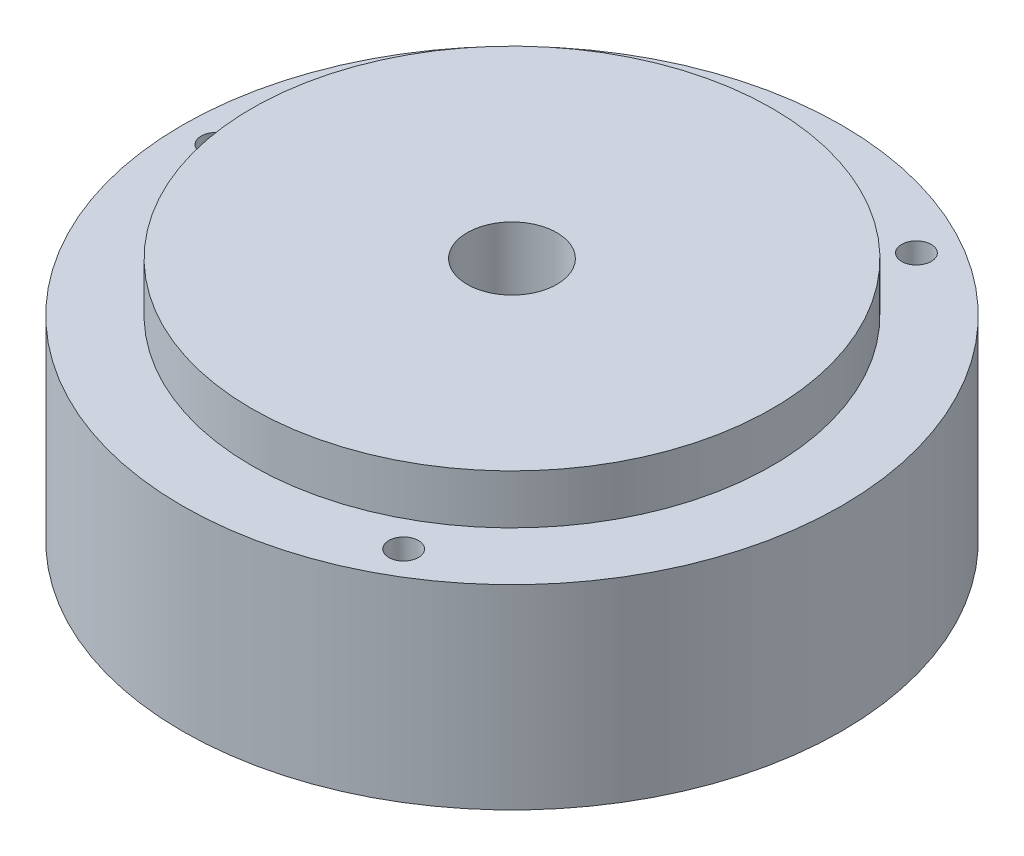
SolidWorks part; units mm, degrees
ref_plane "Alzado" through (0, 0, 0) normal (0, 0, 1) x (1, 0, 0)
ref_plane "Planta" through (0, 0, 0) normal (0, 1, 0) x (1, 0, 0)
ref_plane "Vista lateral" through (0, 0, 0) normal (1, 0, 0) x (0, 0, -1)
sketch "Croquis1" plane through (0, 0, 0) normal (0, 0, 1) x (1, 0, 0)
  line L0 (0, 49.6219) -> (0, -38.8565) construction
  line L2 (73.5, -19.267) -> (73.5, 24.233)
  line L3 (73.5, 24.233) -> (58, 24.233)
  line L4 (58, 24.233) -> (58, 35.233)
  line L5 (58, 35.233) -> (0, 35.233)
  line L6 (0, -29.767) -> (0, 35.233)
  line L7 (73.5, -19.267) -> (46.2048, -19.267)
  line L8 (46.2048, -19.267) -> (46.2048, -29.767)
  line L9 (46.2048, -29.767) -> (0, -29.767)
  dimension "D1" = 54.5
  dimension "D2" = 73.5
  dimension "D3" = 11
  dimension "D4" = 65
  dimension "D5" = 58
revolve "Revolución1" add sketch "Croquis1" angle 360 about L0
sketch "Croquis2" plane through (0, 35.233, 0) normal (0, 1, 0) x (1, 0, 0)
  circle A0 centre (0, 0) radius 10
extrude "Cortar-Extruir1" cut sketch "Croquis2" against normal blind 25
sketch "Croquis3" plane through (0, -29.767, 0) normal (0, -1, 0) x (1, 0, 0)
  circle A0 centre (0, 0) radius 20
extrude "Cortar-Extruir2" cut sketch "Croquis3" against normal blind 18
hole_wizard "Refrentado para tornillo con cabeza troncocónica de M61" positions "Croquis5" profile "Croquis4" counterbore size "M6" standard "Ansi Metric" end condition through all
sketch "Croquis5" plane through (0, -19.267, 0) normal (0, -1, 0) x (-1, 0, 0)
  point P0 (66, 0)
  point P7 (-33, -57.1577)
  point P8 (-33, 57.1577)
  point P9 (0, 0)
  dimension "D1" = 66
  dimension "D2" = 3
sketch "Croquis4" plane through (-66, -19.267, 0) normal (1, 0, 0) x (0, 0, -1)
  line L0 (0, 0) -> (0, 54.5)
  line L1 (0, 54.5) -> (3.3, 54.5)
  line L3 (3.3, 54.5) -> (3.3, 4.6)
  line L4 (3.3, 4.6) -> (6.5, 4.6)
  line L5 (6.5, 4.6) -> (6.5, 0)
  line L7 (6.5, 0) -> (0, 0)
  line L11 (0, -6.35) -> (0, 107.95) construction
  dimension "Diámetro de taladro hasta el siguiente" = 6.6
  dimension "Profundidad de taladro hasta el siguiente" = 54.5
  dimension "Diámetro de refrentado" = 13
  dimension "Profundidad de refrentado" = 4.6
sketch "Croquis6" plane through (0, -29.767, 0) normal (0, -1, 0) x (1, 0, 0)
  line L0 (0, 0) -> (-0.0091, -41.07) construction
  line L1 (-0.0091, -41.07) -> (-0.0103, -46.2048) construction
  line L2 (5.8633, -46.2235) -> (-5.8816, -46.2235)
  line L3 (5.8633, -46.2235) -> (5.8633, -41.07)
  line L4 (5.8633, -41.07) -> (-5.8816, -41.07)
  line L5 (-5.8816, -46.2235) -> (-5.8816, -41.07)
  line L6 (-46.2235, -5.8633) -> (-46.2235, 5.8816)
  line L7 (-46.2235, -5.8633) -> (-41.07, -5.8633)
  line L8 (-41.07, -5.8633) -> (-41.07, 5.8816)
  line L9 (-46.2235, 5.8816) -> (-41.07, 5.8816)
  line L10 (-41.07, 0.0091) -> (-46.2048, 0.0103) construction
  line L11 (-5.8633, 46.2235) -> (5.8816, 46.2235)
  line L12 (-5.8633, 46.2235) -> (-5.8633, 41.07)
  line L13 (-5.8633, 41.07) -> (5.8816, 41.07)
  line L14 (5.8816, 46.2235) -> (5.8816, 41.07)
  line L15 (0.0091, 41.07) -> (0.0103, 46.2048) construction
  line L16 (46.2235, 5.8633) -> (46.2235, -5.8816)
  line L17 (46.2235, 5.8633) -> (41.07, 5.8633)
  line L18 (41.07, 5.8633) -> (41.07, -5.8816)
  line L19 (46.2235, -5.8816) -> (41.07, -5.8816)
  line L20 (41.07, -0.0091) -> (46.2048, -0.0103) construction
  circle A1 centre (0, 0) radius 46.2048 construction
  point P32 (0, 0)
  dimension "D1" = 4
extrude "Cortar-Extruir3" cut sketch "Croquis6" against normal up to surface (10.5 mm away) up to face at (-66, -19.267, -6.5)
